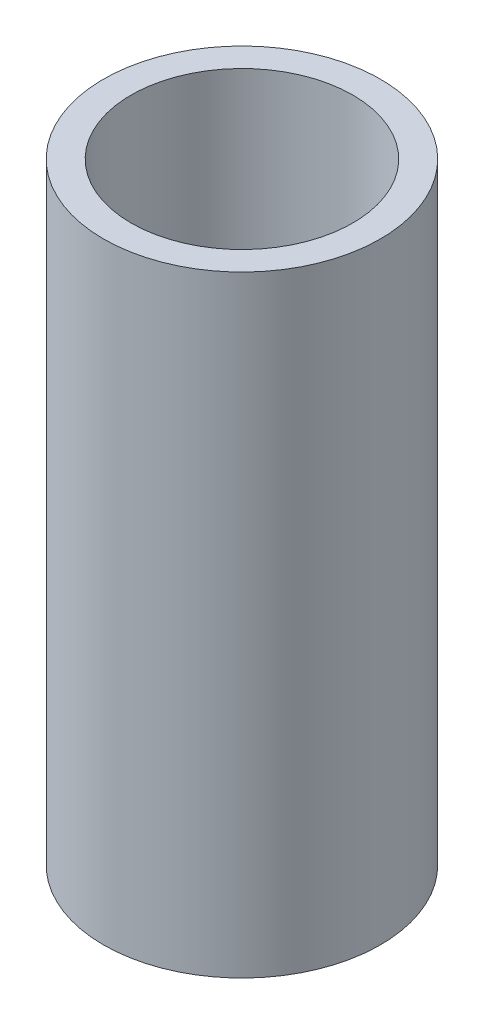
SolidWorks part; units mm, degrees
ref_plane "Front Plane" through (0, 0, 0) normal (0, 0, 1) x (1, 0, 0)
ref_plane "Top Plane" through (0, 0, 0) normal (0, 1, 0) x (1, 0, 0)
ref_plane "Right Plane" through (0, 0, 0) normal (1, 0, 0) x (0, 0, -1)
sketch "Sketch1" plane through (0, 0, 0) normal (0, 1, 0) x (1, 0, 0)
  circle A0 centre (0, 0) radius 1.75
  circle A1 centre (0, 0) radius 2.185
  dimension "D1" = 3.5
  dimension "D2" = 4.37
extrude "Boss-Extrude1" add sketch "Sketch1" along normal blind 9.65
